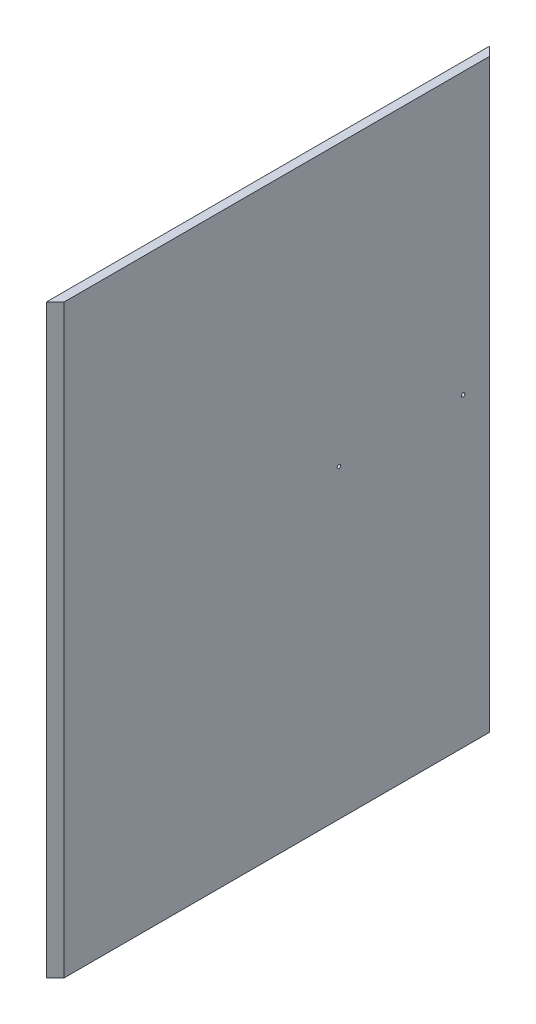
SolidWorks part; units mm, degrees
material "ABS"
ref_plane "Alzado" through (0, 0, 0) normal (0, 0, 1) x (1, 0, 0)
ref_plane "Planta" through (0, 0, 0) normal (0, 1, 0) x (1, 0, 0)
ref_plane "Vista lateral" through (0, 0, 0) normal (1, 0, 0) x (0, 0, -1)
sketch "Croquis1" plane through (0, 0, 0) normal (0, 1, 0) x (1, 0, 0)
  line L0 (0, 0) -> (0, 250)
  line L1 (0, 250) -> (-5, 250)
  line L2 (-5, 250) -> (-5, 0)
  line L3 (-5, 0) -> (0, 0)
  dimension "D1" = 250
  dimension "D2" = 250
  dimension "D3" = 5
extrude "Saliente-Extruir1" add sketch "Croquis1" along normal blind 330
sketch "Croquis2" plane through (0, 330, 0) normal (0, 1, 0) x (1, 0, 0)
  line L0 (0, 250) -> (0, 245)
  line L1 (0, 0) -> (0, 250) construction
  line L2 (0, 245) -> (-5, 250)
  line L3 (-5, 250) -> (0, 250)
  line L4 (-5, 0) -> (0, 5)
  line L5 (0, 5) -> (0, 0)
  line L6 (0, 0) -> (-5, 0)
  dimension "D1" = 5
  dimension "D2" = 5
extrude "Cortar-Extruir1" cut sketch "Croquis2" against normal up to next
sketch "Croquis6" plane through (-5, 0, 0) normal (-1, 0, 0) x (0, 0, 1)
  line L0 (-250, 330) -> (-250, 0) construction
  line L1 (-250, 0) -> (0, 0) construction
  circle A0 centre (-230, 172.2) radius 1
  circle A1 centre (-160, 172.2) radius 1
  dimension "D1" = 2
  dimension "D4" = 2
  dimension "D2" = 20
  dimension "D3" = 172.2
  dimension "D5" = 70
extrude "Cortar-Extruir2" cut sketch "Croquis6" against normal up to next
